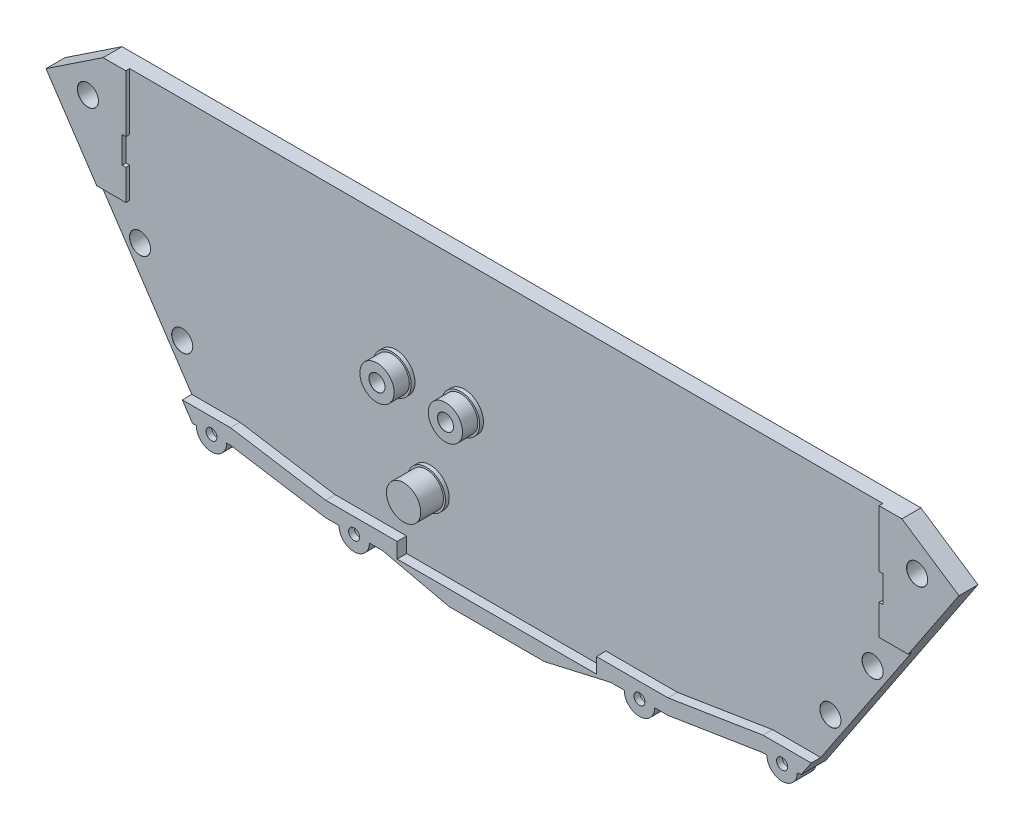
SolidWorks part; units mm, degrees
ref_plane "前视基准面" through (0, 0, 0) normal (0, 0, 1) x (1, 0, 0)
ref_plane "上视基准面" through (0, 0, 0) normal (0, 1, 0) x (1, 0, 0)
ref_plane "右视基准面" through (0, 0, 0) normal (1, 0, 0) x (0, 0, -1)
sketch "草图2" plane through (0, 0, 0) normal (0, 0, 1) x (1, 0, 0)
  line L0 (0, 0) -> (0, 68.1582) construction
  line L1 (80, 0) -> (-80, 0)
  line L2 (-80, 0) -> (-120, 60)
  line L3 (-120, 60) -> (-105, 70)
  line L4 (-105, 70) -> (105, 70)
  line L5 (120, 60) -> (105, 70)
  line L6 (80, 0) -> (120, 60)
  point P10 (0, 70)
  point P12 (0, 0)
  dimension "D1" = 210
  dimension "D2" = 70
  dimension "D3" = 15
  dimension "D4" = 60
  dimension "D5" = 40
extrude "凸台-拉伸1" add sketch "草图2" along normal blind 4
sketch "草图3" plane through (0, 0, 4) normal (0, 0, 1) x (1, 0, 0)
  line L0 (0, 70) -> (0, 0) construction
  line L1 (105, 70) -> (99, 70)
  line L3 (105, 70) -> (-105, 70) construction
  line L5 (-105, 70) -> (-120, 60) construction
  line L6 (-120, 60) -> (-105, 70)
  line L7 (-105, 70) -> (-99, 70)
  line L8 (-99, 70) -> (-99, 55)
  line L9 (-99, 55) -> (-100, 55)
  line L10 (-100, 55) -> (-100, 48)
  line L11 (-100, 48) -> (-99, 48)
  line L12 (-99, 48) -> (-99, 40)
  line L21 (99, 70) -> (99, 55)
  line L22 (99, 55) -> (100, 55)
  line L23 (100, 55) -> (100, 48)
  line L24 (100, 48) -> (99, 48)
  line L25 (99, 48) -> (99, 40)
  line L27 (120, 60) -> (105, 70) construction
  line L28 (120, 60) -> (105, 70)
  line L29 (-120, 60) -> (-80, 0) construction
  line L30 (-120, 60) -> (-106.6667, 40)
  line L31 (-106.6667, 40) -> (-99, 40)
  line L32 (120, 60) -> (106.6667, 40)
  line L33 (80, 0) -> (120, 60) construction
  line L34 (106.6667, 40) -> (99, 40)
  point P7 (-99, 62.5)
  dimension "D2" = 7
  dimension "D3" = 15
  dimension "D4" = 99
  dimension "D5" = 99
  dimension "D6" = 1
  dimension "D7" = 200
  dimension "D8" = 1
  dimension "D9" = 1
  dimension "D10" = 15
  dimension "D11" = 30
  dimension "D12" = 7
  dimension "D13" = 30
extrude "凸台-拉伸2" add sketch "草图3" along normal blind 1
hole_wizard "M5 间隙孔1" positions "草图15" profile "草图14" hole size "M5" standard "ISO" end condition through all
sketch "草图15" plane through (0, 0, 5) normal (0, 0, 1) x (1, 0, 0)
  line L0 (0, 0) -> (0, 70) construction
  line L3 (-99, 70) -> (-105, 70) construction
  line L5 (-99, 55) -> (-99, 70) construction
  point P0 (-109, 59.5)
  point P22 (109, 59.5)
  dimension "D1" = 10.5
  dimension "D2" = 10
sketch "草图14" plane through (-109, 59.5, 5) normal (1, 0, 0) x (0, -1, 0)
  line L0 (0, 0) -> (0, 5)
  line L1 (0, 5) -> (2.75, 5)
  line L2 (2.75, 5) -> (2.75, 0.025)
  line L3 (2.75, 0.025) -> (2.775, 0)
  line L5 (2.775, 0) -> (0, 0)
  line L6 (-2.75, 0.025) -> (-2.775, 0) construction
  line L11 (0, -6.35) -> (0, 107.95) construction
  dimension "通孔孔直径" = 5.5
  dimension "通孔孔深度" = 5
  dimension "近端锥形沉头孔直径" = 5.55
  dimension "近端锥形沉头孔角度" = 90
sketch "草图21" plane through (0, 0, 4) normal (0, 0, 1) x (1, 0, 0)
  line L0 (0, 0) -> (0, 92.551) construction
  line L1 (-80, 0) -> (80, 0) construction
  line L2 (-70, 0) -> (-45, -4)
  line L3 (-45, -4) -> (-30, -4)
  line L4 (-30, -4) -> (-12.5, -8)
  line L5 (-12.5, -8) -> (12.5, -8)
  line L6 (70, 0) -> (45, -4)
  line L7 (45, -4) -> (30, -4)
  line L8 (30, -4) -> (12.5, -8)
  line L10 (-70, 0) -> (-80, 0)
  line L11 (-80, 0) -> (-82.6667, 4)
  line L12 (-106.6667, 40) -> (-80, 0) construction
  line L13 (-82.6667, 4) -> (-70, 4)
  line L14 (-70, 4) -> (-45, 0)
  line L15 (-45, 0) -> (-26.1969, 0)
  line L16 (-26.1969, 0) -> (-26.1969, -4)
  line L17 (-26.1969, -4) -> (26.1969, -4)
  line L18 (82.6667, 4) -> (70, 4)
  line L19 (70, 4) -> (45, 0)
  line L20 (45, 0) -> (26.1969, 0)
  line L21 (26.1969, 0) -> (26.1969, -4)
  line L22 (70, 0) -> (80, 0)
  line L23 (80, 0) -> (82.6667, 4)
  point P20 (0, -8)
  point P29 (0, -4)
  dimension "D1" = 10
  dimension "D2" = 25
  dimension "D3" = 4
  dimension "D4" = 15
  dimension "D5" = 12.5
  dimension "D6" = 8
  dimension "D7" = 4
extrude "凸台-拉伸3" add sketch "草图21" along normal blind 6.5 from offset 4 offset against normal yes
sketch "草图22" plane through (0, 0, 0) normal (0, -1, 0) x (1, 0, 0)
  line L4 (26.1969, 0) -> (26.1969, 4)
  line L5 (26.1969, 4) -> (-26.1969, 4)
  line L6 (-26.1969, 4) -> (-26.1969, 0)
  line L7 (-26.1969, 0) -> (26.1969, 0)
  line L8 (26.1969, 0) -> (26.1969, 4)
  line L9 (26.1969, 4) -> (-26.1969, 4)
  line L10 (-26.1969, 4) -> (-26.1969, 0)
  line L11 (-26.1969, 0) -> (26.1969, 0)
  dimension "D1" = 0
extrude "凸台-拉伸4" add sketch "草图22" along normal blind 4
sketch "草图23" plane through (0, 0, 6.5) normal (0, 0, 1) x (1, 0, 0)
  line L0 (-80, 0) -> (-70, 0) construction
  line L1 (-45, -4) -> (-30, -4) construction
  line L2 (30, -4) -> (45, -4) construction
  line L3 (70, 0) -> (80, 0) construction
  circle A0 centre (-75, 0) radius 4
  circle A1 centre (-37.5, -4) radius 4
  circle A2 centre (37.5, -4) radius 4
  circle A3 centre (75, 0) radius 4
extrude "凸台-拉伸5" add sketch "草图23" against normal blind 5
hole_wizard "M2.5 间隙孔1" positions "草图25" profile "草图26" hole size "M2.5" standard "ISO"
sketch "草图25" plane through (0, 0, 0) normal (0, 0, -1) x (-1, 0, 0)
  point P0 (-75, 0)
  point P3 (-37.5, -4)
  point P6 (37.5, -4)
  point P10 (75, 0)
sketch "草图26" plane through (75, 0, 0) normal (1, 0, 0) x (0, 1, 0)
  line L0 (0, 0) -> (0, 10.8712)
  line L1 (0, 10.8712) -> (1.45, 10)
  line L2 (1.45, 10) -> (1.45, 0.025)
  line L3 (1.45, 0.025) -> (1.475, 0)
  line L5 (1.475, 0) -> (0, 0)
  line L6 (-1.45, 0.025) -> (-1.475, 0) construction
  line L10 (0, 10.8712) -> (-1.45, 10) construction
  line L11 (0, -6.35) -> (0, 107.95) construction
  dimension "孔直径" = 2.9
  dimension "孔深度" = 10
  dimension "近端锥形沉头孔直径" = 2.95
  dimension "近端锥形沉头孔角度" = 90
  dimension "导头角度" = 118
sketch "草图27" plane through (0, 0, 0) normal (0, 0, -1) x (-1, 0, 0)
  circle A5 centre (-75, 0) radius 2.5
  circle A6 centre (-37.5, -4) radius 2.5
  circle A7 centre (75, 0) radius 2.5
  circle A8 centre (37.5, -4) radius 2.5
  dimension "D1" = 5
  dimension "D2" = 5
  dimension "D3" = 5
  dimension "D4" = 5
extrude "切除-拉伸4" cut sketch "草图27" against normal blind 5
sketch "草图28" plane through (0, 0, 4) normal (0, 0, 1) x (1, 0, 0)
  line L0 (-12.5, -8) -> (12.5, -8) construction
  line L2 (-20, 14.25) -> (-20, 34.5408) construction
  circle A0 centre (-20, 14.25) radius 5
  circle A1 centre (-29, 36) radius 5
  circle A2 centre (-11, 36) radius 5
  dimension "D3" = 10
  dimension "D4" = 10
  dimension "D1" = 22.25
  dimension "D2" = 20
  dimension "D5" = 9
  dimension "D6" = 44
extrude "凸台-拉伸6" add sketch "草图28" along normal blind 1
sketch "草图29" plane through (0, 0, 5) normal (0, 0, 1) x (1, 0, 0)
  circle A0 centre (-20, 14.25) radius 4.5
  dimension "D1" = 9
extrude "凸台-拉伸7" add sketch "草图29" along normal blind 6
sketch "草图30" plane through (0, 0, 5) normal (0, 0, 1) x (1, 0, 0)
  circle A0 centre (-11, 36) radius 4.5
  circle A1 centre (-29, 36) radius 4.5
  dimension "D1" = 9
  dimension "D2" = 9
extrude "凸台-拉伸8" add sketch "草图30" along normal blind 4
hole_wizard "M5 螺纹孔的螺纹孔钻头1" positions "草图31" profile "草图32" hole size "M5" standard "ISO" end condition through all
sketch "草图31" plane through (0, 0, 9) normal (0, 0, 1) x (1, 0, 0)
  point P0 (-29, 36)
  point P3 (-11, 36)
sketch "草图32" plane through (-29, 36, 9) normal (1, 0, 0) x (0, -1, 0)
  line L0 (0, 0) -> (0, 9)
  line L1 (0, 9) -> (2.1, 9)
  line L2 (2.1, 9) -> (2.1, 0.025)
  line L3 (2.1, 0.025) -> (2.125, 0)
  line L5 (2.125, 0) -> (0, 0)
  line L6 (-2.1, 0.025) -> (-2.125, 0) construction
  line L11 (0, -6.35) -> (0, 107.95) construction
  dimension "通孔孔直径" = 4.2
  dimension "通孔孔深度" = 9
  dimension "近端锥形沉头孔直径" = 4.25
  dimension "近端锥形沉头孔角度" = 90
hole_wizard "M5 间隙孔2" positions "草图34" profile "草图35" hole size "M5" standard "ISO"
sketch "草图34" plane through (0, 0, 4) normal (0, 0, 1) x (1, 0, 0)
  line L0 (-106.6667, 40) -> (-82.6667, 4) construction
  line L1 (-80, 0) -> (-79, 0) construction
  line L2 (0, 0) -> (0, 26.2083) construction
  point P0 (-96.2866, 31.641)
  point P2 (-85.1926, 15)
  point P22 (96.2866, 31.641)
  point P23 (85.1926, 15)
  dimension "D1" = 4
  dimension "D2" = 20
  dimension "D3" = 4
  dimension "D4" = 15
sketch "草图35" plane through (-96.2866, 31.641, 4) normal (1, 0, 0) x (0, -1, 0)
  line L0 (0, 0) -> (0, 11.6524)
  line L1 (0, 11.6524) -> (2.75, 10)
  line L2 (2.75, 10) -> (2.75, 0.025)
  line L3 (2.75, 0.025) -> (2.775, 0)
  line L5 (2.775, 0) -> (0, 0)
  line L6 (-2.75, 0.025) -> (-2.775, 0) construction
  line L10 (0, 11.6524) -> (-2.75, 10) construction
  line L11 (0, -6.35) -> (0, 107.95) construction
  dimension "孔直径" = 5.5
  dimension "孔深度" = 10
  dimension "近端锥形沉头孔直径" = 5.55
  dimension "近端锥形沉头孔角度" = 90
  dimension "导头角度" = 118
